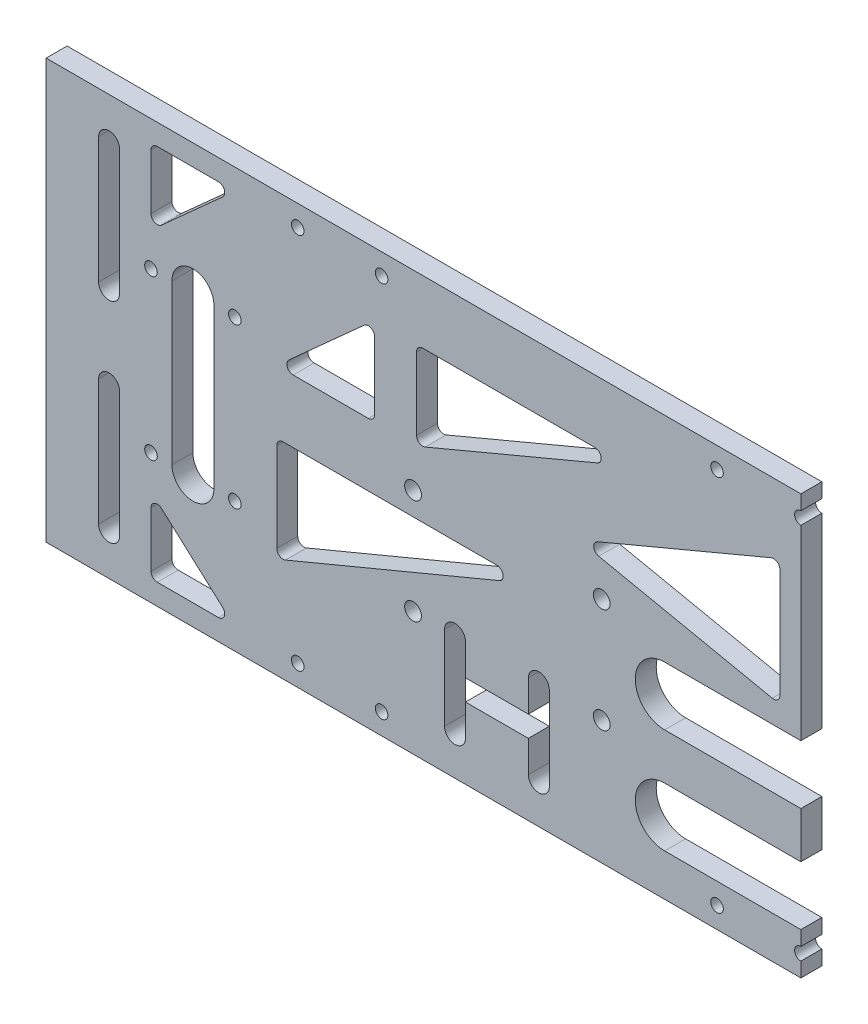
SolidWorks part; units mm, degrees
material "A-玻璃纤维"
ref_plane "前视基准面" through (0, 0, 0) normal (0, 0, 1) x (1, 0, 0)
ref_plane "上视基准面" through (0, 0, 0) normal (0, 1, 0) x (1, 0, 0)
ref_plane "右视基准面" through (0, 0, 0) normal (1, 0, 0) x (0, 0, -1)
sketch "草图1" plane through (0, 0, 0) normal (0, 0, 1) x (1, 0, 0)
  line L1 (0, 0) -> (320, 0)
  line L2 (0, 0) -> (0, 121)
  line L3 (0, 121) -> (320, 121)
  line L4 (320, 0) -> (320, 121)
  dimension "D1" = 320
  dimension "D2" = 121
extrude "凸台-拉伸1" add sketch "草图1" along normal blind 5
sketch "草图2" plane through (0, 0, 5) normal (0, 0, 1) x (1, 0, 0)
  line L0 (160, 121) -> (160, 0) construction
  line L1 (320, 121) -> (0, 121) construction
  line L2 (0, 0) -> (320, 0) construction
  line L3 (0, 121) -> (0, 0) construction
  line L4 (30, 0) -> (35, 0)
  line L5 (30, 0) -> (30, 30)
  line L6 (30, 30) -> (35, 30)
  line L7 (35, 0) -> (35, 30)
  line L8 (285, 0) -> (285, 30)
  line L9 (290, 30) -> (285, 30)
  line L10 (290, 0) -> (290, 30)
  line L11 (290, 0) -> (285, 0)
  dimension "D1" = 30
  dimension "D2" = 30
  dimension "D3" = 5
extrude "切除-拉伸1" cut sketch "草图2" against normal through all
sketch "草图3" plane through (0, 0, 5) normal (0, 0, 1) x (1, 0, 0)
  line L0 (40, 116) -> (60, 116) construction
  line L1 (160, 121) -> (160, 0) construction
  line L2 (320, 121) -> (0, 121) construction
  line L3 (35, 0) -> (285, 0) construction
  line L4 (140, 116) -> (160, 116) construction
  line L5 (0, 121) -> (0, 0) construction
  line L6 (280, 116) -> (260, 116) construction
  circle A0 centre (40, 116) radius 1.5
  circle A1 centre (60, 116) radius 1.5
  circle A2 centre (140, 116) radius 1.5
  circle A3 centre (160, 116) radius 1.5
  circle A4 centre (260, 116) radius 1.5
  circle A5 centre (280, 116) radius 1.5
  circle A6 centre (180, 116) radius 1.5
  dimension "D5" = 3
  dimension "D1" = 40
  dimension "D2" = 5
  dimension "D3" = 20
  dimension "D4" = 20
extrude "切除-拉伸2" cut sketch "草图3" against normal through all
sketch "草图4" plane through (0, 0, 5) normal (0, 0, 1) x (1, 0, 0)
  line L0 (160, 121) -> (160, 0) construction
  line L1 (5, 90) -> (25, 90) construction
  line L2 (5, 90) -> (5, 10) construction
  line L3 (5, 10) -> (25, 10) construction
  line L4 (25, 90) -> (25, 10) construction
  line L5 (320, 121) -> (0, 121) construction
  line L6 (35, 0) -> (285, 0) construction
  line L7 (0, 0) -> (30, 0) construction
  line L8 (0, 121) -> (0, 0) construction
  line L10 (295, 90) -> (295, 10) construction
  line L11 (315, 10) -> (295, 10) construction
  line L12 (315, 90) -> (315, 10) construction
  line L13 (315, 90) -> (295, 90) construction
  circle A0 centre (5, 90) radius 1.5
  circle A1 centre (25, 90) radius 1.5
  circle A2 centre (5, 10) radius 1.5
  circle A3 centre (25, 10) radius 1.5
  circle A4 centre (295, 10) radius 1.5
  circle A5 centre (315, 10) radius 1.5
  circle A6 centre (295, 90) radius 1.5
  circle A7 centre (315, 90) radius 1.5
  dimension "D5" = 3
  dimension "D1" = 10
  dimension "D2" = 80
  dimension "D3" = 5
  dimension "D4" = 20
extrude "切除-拉伸3" cut sketch "草图4" against normal through all
sketch "草图6" plane through (0, 0, 5) normal (0, 0, 1) x (1, 0, 0)
  line L0 (160, 121) -> (160, 0) construction
  line L1 (320, 121) -> (0, 121) construction
  line L2 (35, 0) -> (285, 0) construction
  line L3 (127.5, 63) -> (192.5, 63) construction
  line L4 (112.5, 50.5) -> (207.5, 50.5) construction
  line L5 (112.5, 50.5) -> (112.5, 75.5) construction
  line L6 (112.5, 75.5) -> (207.5, 75.5) construction
  line L7 (207.5, 50.5) -> (207.5, 75.5) construction
  line L8 (112.5, 50.5) -> (207.5, 75.5) construction
  line L9 (112.5, 75.5) -> (207.5, 50.5) construction
  line L10 (127.5, 70) -> (192.5, 70)
  line L11 (127.5, 56) -> (192.5, 56)
  circle A0 centre (112.5, 75.5) radius 2
  circle A1 centre (207.5, 75.5) radius 2
  circle A2 centre (207.5, 50.5) radius 2
  circle A3 centre (112.5, 50.5) radius 2
  arc A4 (127.5, 70) -> (127.5, 56) centre (127.5, 63) ccw
  arc A5 (192.5, 56) -> (192.5, 70) centre (192.5, 63) ccw
  point P6 (160, 63)
  point P17 (160, 63)
  dimension "D1" = 4
  dimension "D5" = 7
  dimension "D2" = 25
  dimension "D3" = 95
  dimension "D4" = 45.5
  dimension "D6" = 15
extrude "切除-拉伸5" cut sketch "草图6" against normal through all
sketch "草图5" plane through (0, 0, 5) normal (0, 0, 1) x (1, 0, 0)
  line L0 (5, 101.368) -> (5, 114.5)
  line L1 (6.5, 116) -> (21.0911, 116)
  line L2 (22.0945, 113.3851) -> (7.5034, 100.2531)
  line L6 (5, 90) -> (25, 90) construction
  line L7 (0, 121) -> (0, 0) construction
  line L8 (320, 121) -> (0, 121) construction
  line L9 (38.9089, 85) -> (56.8333, 85)
  line L10 (58.3333, 86.5) -> (58.3333, 102.632)
  line L11 (55.8299, 103.7469) -> (37.9055, 87.6149)
  line L12 (160, 121) -> (160, 0) construction
  line L13 (35, 0) -> (285, 0) construction
  line L14 (35, 68.5) -> (35, 47.25)
  line L15 (35, 0) -> (285, 0)
  line L16 (35, 0) -> (35, 30)
  line L17 (35, 30) -> (285, 30)
  line L18 (285, 0) -> (285, 30)
  line L19 (37.0769, 45.8654) -> (88.0769, 67.1154)
  line L20 (87.5, 70) -> (36.5, 70)
  line L24 (68.3333, 87.2569) -> (68.3333, 104.5)
  line L25 (69.8333, 106) -> (110.8883, 106)
  line L26 (111.4691, 103.117) -> (70.4142, 85.874)
  line L27 (111.7889, 84.0154) -> (153.1936, 75.3769)
  line L28 (155, 76.8453) -> (155, 102.8738)
  line L29 (152.9192, 104.2567) -> (111.5144, 86.8668)
  line L30 (315, 90) -> (295, 90) construction
  line L31 (167.0808, 104.2567) -> (208.4856, 86.8668)
  line L32 (165, 76.8453) -> (165, 102.8738)
  line L33 (208.2111, 84.0154) -> (166.8064, 75.3769)
  line L34 (208.5309, 103.117) -> (249.5858, 85.874)
  line L35 (250.1667, 106) -> (209.1117, 106)
  line L36 (251.6667, 87.2569) -> (251.6667, 104.5)
  line L40 (232.5, 70) -> (283.5, 70)
  line L41 (282.9231, 45.8654) -> (231.9231, 67.1154)
  line L42 (285, 68.5) -> (285, 47.25)
  line L43 (264.1701, 103.7469) -> (282.0945, 87.6149)
  line L44 (261.6667, 86.5) -> (261.6667, 102.632)
  line L45 (281.0911, 85) -> (263.1667, 85)
  line L46 (297.9055, 113.3851) -> (312.4966, 100.2531)
  line L47 (313.5, 116) -> (298.9089, 116)
  line L48 (315, 101.368) -> (315, 114.5)
  line L52 (192.5, 70) -> (127.5, 70) construction
  arc A2 (155, 102.8738) -> (152.9192, 104.2567) centre (153.5, 102.8738) ccw
  arc A4 (21.0911, 116) -> (22.0945, 113.3851) centre (21.0911, 114.5) cw
  arc A5 (5, 101.368) -> (7.5034, 100.2531) centre (6.5, 101.368) ccw
  arc A6 (5, 114.5) -> (6.5, 116) centre (6.5, 114.5) cw
  arc A7 (56.8333, 85) -> (58.3333, 86.5) centre (56.8333, 86.5) ccw
  arc A8 (38.9089, 85) -> (37.9055, 87.6149) centre (38.9089, 86.5) cw
  arc A9 (58.3333, 102.632) -> (55.8299, 103.7469) centre (56.8333, 102.632) ccw
  arc A10 (88.0769, 67.1154) -> (87.5, 70) centre (87.5, 68.5) ccw
  arc A11 (35, 47.25) -> (37.0769, 45.8654) centre (36.5, 47.25) ccw
  arc A12 (35, 68.5) -> (36.5, 70) centre (36.5, 68.5) cw
  arc A17 (153.1936, 75.3769) -> (155, 76.8453) centre (153.5, 76.8453) ccw
  arc A18 (111.7889, 84.0154) -> (111.5144, 86.8668) centre (112.0953, 85.4838) cw
  arc A19 (68.3333, 87.2569) -> (70.4142, 85.874) centre (69.8333, 87.2569) ccw
  arc A20 (68.3333, 104.5) -> (69.8333, 106) centre (69.8333, 104.5) cw
  arc A21 (110.8883, 106) -> (111.4691, 103.117) centre (110.8883, 104.5) cw
  arc A22 (209.1117, 106) -> (208.5309, 103.117) centre (209.1117, 104.5) ccw
  arc A23 (251.6667, 104.5) -> (250.1667, 106) centre (250.1667, 104.5) ccw
  arc A24 (251.6667, 87.2569) -> (249.5858, 85.874) centre (250.1667, 87.2569) cw
  arc A25 (208.2111, 84.0154) -> (208.4856, 86.8668) centre (207.9047, 85.4838) ccw
  arc A26 (166.8064, 75.3769) -> (165, 76.8453) centre (166.5, 76.8453) cw
  arc A30 (285, 68.5) -> (283.5, 70) centre (283.5, 68.5) ccw
  arc A31 (285, 47.25) -> (282.9231, 45.8654) centre (283.5, 47.25) cw
  arc A32 (231.9231, 67.1154) -> (232.5, 70) centre (232.5, 68.5) cw
  arc A33 (261.6667, 102.632) -> (264.1701, 103.7469) centre (263.1667, 102.632) cw
  arc A34 (281.0911, 85) -> (282.0945, 87.6149) centre (281.0911, 86.5) ccw
  arc A35 (263.1667, 85) -> (261.6667, 86.5) centre (263.1667, 86.5) cw
  arc A36 (315, 114.5) -> (313.5, 116) centre (313.5, 114.5) ccw
  arc A37 (315, 101.368) -> (312.4966, 100.2531) centre (313.5, 101.368) cw
  arc A38 (298.9089, 116) -> (297.9055, 113.3851) centre (298.9089, 114.5) ccw
  arc A39 (165, 102.8738) -> (167.0808, 104.2567) centre (166.5, 102.8738) cw
  point P23 (25, 116)
  point P26 (5, 98)
  point P29 (5, 116)
  point P40 (35, 85)
  point P43 (58.3333, 106)
  point P56 (95, 70)
  point P59 (35, 45)
  point P62 (35, 70)
  point P84 (155, 105.1307)
  point P87 (155, 75)
  point P90 (107.0698, 85)
  point P93 (68.3333, 85)
  point P96 (68.3333, 106)
  point P99 (118.3333, 106)
  point P156 (201.6667, 106)
  point P157 (251.6667, 106)
  point P158 (251.6667, 85)
  point P159 (212.9302, 85)
  point P160 (165, 75)
  point P161 (165, 105.1307)
  point P162 (285, 70)
  point P163 (285, 45)
  point P164 (225, 70)
  point P165 (261.6667, 106)
  point P166 (285, 85)
  point P167 (315, 116)
  point P168 (315, 98)
  point P169 (295, 116)
  point P186 (20, 15)
  point P189 (8, 15)
  point P192 (20, 25)
  point P202 (300, 25)
  point P203 (312, 15)
  point P204 (300, 15)
  dimension "D8" = 1.5
  dimension "D12" = 1.5
  dimension "D16" = 1.5
  dimension "D27" = 1.5
  dimension "D4" = 5
  dimension "D5" = 5
  dimension "D6" = 20
  dimension "D7" = 18
  dimension "D9" = 5
  dimension "D10" = 10
  dimension "D11" = 10
  dimension "D13" = 15
  dimension "D14" = 15
  dimension "D15" = 60
  dimension "D21" = 15
  dimension "D22" = 10
  dimension "D23" = 50
  dimension "D24" = 15
  dimension "D25" = 10
  dimension "D26" = 5
  dimension "D29" = 8
  dimension "D31" = 10
extrude "切除-拉伸4" cut sketch "草图5" against normal through all
sketch "草图7" plane through (0, 0, 0) normal (0, 0, -1) x (-1, 0, 0)
  line L0 (-290, 0) -> (-290, 30)
  line L1 (-290, 30) -> (-30, 30)
  line L2 (-30, 30) -> (-30, 0)
  line L3 (-30, 0) -> (-290, 0)
extrude "凸台-拉伸2" add sketch "草图7" against normal blind 5
sketch "草图8" plane through (0, 0, 0) normal (0, 0, -1) x (-1, 0, 0)
  line L0 (-320, 0) -> (-320, 21)
  line L1 (-320, 0) -> (-320, 121) construction
  line L2 (-320, 21) -> (0, 21)
  line L3 (0, 121) -> (0, 0) construction
  line L4 (0, 21) -> (0, 0)
  line L5 (0, 0) -> (-320, 0)
extrude "切除-拉伸6" cut sketch "草图8" against normal blind 5
sketch "草图9" plane through (0, 0, 0) normal (0, 0, -1) x (-1, 0, 0)
  line L0 (-160, 21) -> (-335, 21)
  line L1 (0, 21) -> (-320, 21) construction
  line L2 (-335, 21) -> (-335, 121)
  line L3 (-335, 121) -> (15, 121)
  line L4 (15, 121) -> (15, 21)
  line L5 (15, 21) -> (-160, 21)
  line L6 (0, 21) -> (0, 121)
  line L7 (-320, 21) -> (-320, 121)
extrude "凸台-拉伸3" add sketch "草图9" against normal blind 5 contours L0 L7 L3 L2 | L6 L5 L4 L3
sketch "草图10" plane through (0, 0, 0) normal (0, 0, -1) x (-1, 0, 0)
  line L0 (-335, 71) -> (-325, 71)
  line L1 (-335, 21) -> (-335, 121) construction
  line L2 (-325, 71) -> (-325, 121)
  line L3 (-335, 121) -> (15, 121) construction
  line L4 (-325, 71) -> (-325, 21)
  line L5 (15, 21) -> (-335, 21) construction
  line L6 (15, 71) -> (5, 71)
  line L7 (15, 121) -> (15, 21) construction
  line L8 (5, 71) -> (5, 121)
  line L9 (5, 71) -> (5, 21)
  line L10 (-325, 71) -> (-325, 81)
  line L11 (-325, 81) -> (-325, 111)
  line L12 (-325, 71) -> (-325, 61)
  line L13 (-325, 61) -> (-325, 31)
  line L14 (-325, 81) -> (-325, 111) construction
  line L15 (-327.5, 81) -> (-327.5, 111)
  line L16 (-322.5, 81) -> (-322.5, 111)
  line L17 (-325, 61) -> (-325, 31) construction
  line L18 (-322.5, 61) -> (-322.5, 31)
  line L19 (-327.5, 61) -> (-327.5, 31)
  line L20 (-160, 21) -> (-160, 121)
  line L21 (5, 61) -> (5, 31) construction
  line L22 (2.5, 61) -> (2.5, 31)
  line L23 (7.5, 61) -> (7.5, 31)
  line L24 (5, 81) -> (5, 111) construction
  line L25 (7.5, 81) -> (7.5, 111)
  line L26 (2.5, 81) -> (2.5, 111)
  arc A0 (-327.5, 81) -> (-322.5, 81) centre (-325, 81) ccw
  arc A1 (-322.5, 111) -> (-327.5, 111) centre (-325, 111) ccw
  arc A2 (-322.5, 61) -> (-327.5, 61) centre (-325, 61) ccw
  arc A3 (-327.5, 31) -> (-322.5, 31) centre (-325, 31) ccw
  arc A4 (2.5, 61) -> (7.5, 61) centre (5, 61) cw
  arc A5 (7.5, 31) -> (2.5, 31) centre (5, 31) cw
  arc A6 (7.5, 81) -> (2.5, 81) centre (5, 81) cw
  arc A7 (2.5, 111) -> (7.5, 111) centre (5, 111) cw
  point P20 (-325, 96)
  point P25 (-325, 46)
  point P34 (5, 46)
  point P41 (5, 96)
  dimension "D1" = 10
  dimension "D2" = 10
  dimension "D3" = 30
  dimension "D4" = 10
  dimension "D5" = 30
extrude "切除-拉伸7" cut sketch "草图10" against normal blind 5 contours L16 A1 L2 L10 A0 | L2 A1 L15 A0 L10 | L4 A3 L18 A2 L12 | L19 A3 L4 L12 A2 | A7 L8 A6 L25 | A7 L26 A6 L8 | A5 L23 A4 L9 | A5 L9 A4 L22
sketch "草图13" plane through (0, 0, 0) normal (0, 0, -1) x (-1, 0, 0)
  line L12 (-192.5, 63) -> (-192.5, 38)
  line L13 (-127.5, 63) -> (-127.5, 38)
  line L14 (-192.5, 38) -> (-127.5, 38) construction
  line L15 (-192.5, 45) -> (-127.5, 45)
  line L16 (-192.5, 31) -> (-127.5, 31)
  line L18 (-305, 63.5) -> (-305, 83.5)
  line L19 (-305, 63.5) -> (-305, 48.5)
  line L23 (-160, 21) -> (-160, 121)
  line L24 (15, 21) -> (-335, 21) construction
  line L25 (-335, 121) -> (15, 121) construction
  arc A1 (-192.5, 45) -> (-192.5, 31) centre (-192.5, 38) ccw
  arc A2 (-127.5, 31) -> (-127.5, 45) centre (-127.5, 38) ccw
  point P16 (-160, 38)
  dimension "D1" = 25
  dimension "D3" = 15
  dimension "D2" = 25
  dimension "D4" = 20
extrude "切除-拉伸8" cut sketch "草图13" against normal blind 5
sketch "草图15" plane through (0, 0, 0) normal (0, 0, -1) x (-1, 0, 0)
  line L0 (-313.5, 116) -> (-298.9089, 116)
  line L1 (-297.9055, 113.3851) -> (-312.4966, 100.2531)
  line L2 (-315, 114.5) -> (-315, 101.368)
  line L3 (-21.0911, 116) -> (-6.5, 116)
  line L4 (-5, 114.5) -> (-5, 101.368)
  line L5 (-7.5034, 100.2531) -> (-22.0945, 113.3851)
  line L6 (-335, 71) -> (15, 71)
  line L7 (-335, 21) -> (-335, 121) construction
  line L8 (15, 121) -> (15, 21) construction
  line L9 (-21.0911, 26) -> (-6.5, 26)
  line L10 (-5, 27.5) -> (-5, 40.632)
  line L11 (-7.5034, 41.7469) -> (-22.0945, 28.6149)
  line L12 (-315, 27.5) -> (-315, 40.632)
  line L13 (-313.5, 26) -> (-298.9089, 26)
  line L14 (-297.9055, 28.6149) -> (-312.4966, 41.7469)
  circle A0 centre (-280, 116) radius 1.5
  circle A1 centre (-260, 116) radius 1.5
  circle A2 centre (-180, 116) radius 1.5
  circle A3 centre (-160, 116) radius 1.5
  circle A4 centre (-140, 116) radius 1.5
  circle A5 centre (-60, 116) radius 1.5
  circle A6 centre (-40, 116) radius 1.5
  circle A7 centre (-25, 90) radius 1.5
  circle A8 centre (-5, 90) radius 1.5
  circle A9 centre (-315, 90) radius 1.5
  circle A10 centre (-295, 90) radius 1.5
  arc A11 (-315, 101.368) -> (-312.4966, 100.2531) centre (-313.5, 101.368) ccw
  arc A12 (-313.5, 116) -> (-315, 114.5) centre (-313.5, 114.5) ccw
  arc A13 (-297.9055, 113.3851) -> (-298.9089, 116) centre (-298.9089, 114.5) ccw
  arc A14 (-21.0911, 116) -> (-22.0945, 113.3851) centre (-21.0911, 114.5) ccw
  arc A15 (-5, 114.5) -> (-6.5, 116) centre (-6.5, 114.5) ccw
  arc A16 (-7.5034, 100.2531) -> (-5, 101.368) centre (-6.5, 101.368) ccw
  circle A17 centre (-25, 52) radius 1.5
  circle A18 centre (-5, 52) radius 1.5
  arc A19 (-5, 27.5) -> (-6.5, 26) centre (-6.5, 27.5) cw
  arc A20 (-7.5034, 41.7469) -> (-5, 40.632) centre (-6.5, 40.632) cw
  arc A21 (-21.0911, 26) -> (-22.0945, 28.6149) centre (-21.0911, 27.5) cw
  circle A22 centre (-40, 26) radius 1.5
  circle A23 centre (-60, 26) radius 1.5
  circle A24 centre (-140, 26) radius 1.5
  circle A25 centre (-160, 26) radius 1.5
  circle A26 centre (-180, 26) radius 1.5
  circle A27 centre (-260, 26) radius 1.5
  circle A28 centre (-280, 26) radius 1.5
  arc A29 (-313.5, 26) -> (-315, 27.5) centre (-313.5, 27.5) cw
  arc A30 (-297.9055, 28.6149) -> (-298.9089, 26) centre (-298.9089, 27.5) cw
  arc A31 (-315, 40.632) -> (-312.4966, 41.7469) centre (-313.5, 40.632) cw
  circle A32 centre (-295, 52) radius 1.5
  circle A33 centre (-315, 52) radius 1.5
extrude "切除-拉伸9" cut sketch "草图15" against normal through all contours A33 | A31 L12 A29 L13 A30 L14 | A32 | A28 | A27 | A26 | A25 | A24 | A23 | A22 | A21 L9 A19 L10 A20 L11 | A18 | A17
sketch "草图16" plane through (0, 0, 0) normal (0, 0, -1) x (-1, 0, 0)
  line L0 (-335, 71) -> (15, 71)
  line L1 (-335, 21) -> (-335, 121) construction
  line L2 (15, 121) -> (15, 21) construction
  line L3 (-315, 90) -> (-295, 90)
  line L4 (-315, 52) -> (-295, 52)
  line L5 (-305, 52) -> (-305, 90)
  line L6 (-305, 52) -> (-305, 90) construction
  line L7 (-310, 52) -> (-310, 90)
  line L8 (-300, 52) -> (-300, 90)
  line L9 (-160, 21) -> (-160, 121)
  line L10 (15, 21) -> (-335, 21) construction
  line L11 (-335, 121) -> (15, 121) construction
  line L12 (-15, 52) -> (-15, 90) construction
  line L13 (-10, 52) -> (-10, 90)
  line L14 (-20, 52) -> (-20, 90)
  arc A0 (-310, 52) -> (-300, 52) centre (-305, 52) ccw
  arc A1 (-300, 90) -> (-310, 90) centre (-305, 90) ccw
  arc A2 (-10, 52) -> (-20, 52) centre (-15, 52) cw
  arc A3 (-20, 90) -> (-10, 90) centre (-15, 90) cw
  point P16 (-305, 71)
  point P29 (-15, 71)
extrude "切除-拉伸10" cut sketch "草图16" against normal through all contours L4 L8 L0 L5 | L4 A0 | L7 L4 L5 L0 | L0 L8 L3 L5 | L7 L0 L5 L3 | L3 A1 | A2 L13 L0 L14 | A3 L14 L0 L13
sketch "草图17" plane through (0, 0, 0) normal (0, 0, -1) x (-1, 0, 0)
  line L0 (-207.5, 50.5) -> (-257.5, 50.5)
  line L1 (-257.5, 50.5) -> (-257.5, 30.5)
  line L2 (-257.5, 30.5) -> (-207.5, 30.5)
  line L3 (-207.5, 30.5) -> (-207.5, 50.5)
  line L4 (-207.5, 40.5) -> (-257.5, 40.5)
  line L5 (-257.5, 50.5) -> (-247.5, 50.5)
  line L6 (-247.5, 50.5) -> (-247.5, 30.5)
  line L7 (-207.5, 50.5) -> (-217.5, 50.5)
  line L8 (-217.5, 50.5) -> (-217.5, 30.5)
  line L9 (-247.5, 50.5) -> (-242.5, 50.5)
  line L10 (-242.5, 50.5) -> (-242.5, 30.5)
  line L11 (-217.5, 50.5) -> (-222.5, 50.5)
  line L12 (-222.5, 50.5) -> (-222.5, 30.5)
  line L13 (-242.5, 50.5) -> (-242.5, 30.5) construction
  line L14 (-240, 50.5) -> (-240, 30.5)
  line L15 (-245, 50.5) -> (-245, 30.5)
  line L16 (-222.5, 50.5) -> (-222.5, 30.5) construction
  line L17 (-220, 50.5) -> (-220, 30.5)
  line L18 (-225, 50.5) -> (-225, 30.5)
  line L19 (-242.5, 40.5) -> (-222.5, 40.5) construction
  line L20 (-242.5, 43) -> (-222.5, 43)
  line L21 (-242.5, 38) -> (-222.5, 38)
  line L22 (-160, 21) -> (-160, 121)
  line L23 (15, 21) -> (-335, 21) construction
  line L24 (-335, 121) -> (15, 121) construction
  line L25 (-97.5, 50.5) -> (-97.5, 30.5) construction
  line L26 (-100, 50.5) -> (-100, 30.5)
  line L27 (-95, 50.5) -> (-95, 30.5)
  line L28 (-77.5, 40.5) -> (-97.5, 40.5) construction
  line L29 (-77.5, 43) -> (-97.5, 43)
  line L30 (-77.5, 38) -> (-97.5, 38)
  line L31 (-77.5, 50.5) -> (-77.5, 30.5) construction
  line L32 (-80, 50.5) -> (-80, 30.5)
  line L33 (-75, 50.5) -> (-75, 30.5)
  arc A0 (-240, 50.5) -> (-245, 50.5) centre (-242.5, 50.5) ccw
  arc A1 (-245, 30.5) -> (-240, 30.5) centre (-242.5, 30.5) ccw
  arc A2 (-220, 50.5) -> (-225, 50.5) centre (-222.5, 50.5) ccw
  arc A3 (-225, 30.5) -> (-220, 30.5) centre (-222.5, 30.5) ccw
  arc A4 (-242.5, 43) -> (-242.5, 38) centre (-242.5, 40.5) ccw
  arc A5 (-222.5, 38) -> (-222.5, 43) centre (-222.5, 40.5) ccw
  arc A6 (-100, 50.5) -> (-95, 50.5) centre (-97.5, 50.5) cw
  arc A7 (-95, 30.5) -> (-100, 30.5) centre (-97.5, 30.5) cw
  arc A8 (-77.5, 43) -> (-77.5, 38) centre (-77.5, 40.5) cw
  arc A9 (-97.5, 38) -> (-97.5, 43) centre (-97.5, 40.5) cw
  arc A10 (-80, 50.5) -> (-75, 50.5) centre (-77.5, 50.5) cw
  arc A11 (-75, 30.5) -> (-80, 30.5) centre (-77.5, 30.5) cw
  point P11 (-242.5, 40.5)
  point P20 (-222.5, 40.5)
  point P25 (-232.5, 40.5)
  point P40 (-97.5, 40.5)
  point P47 (-87.5, 40.5)
  point P54 (-77.5, 40.5)
  dimension "D1" = 20
extrude "切除-拉伸11" cut sketch "草图17" against normal through all contours A11 L33 A8 L30 L32 | A8 L29 L32 L30 | A10 L32 L29 A8 L33 | L32 L29 L27 L30 | A9 L30 L27 L29 | L26 A9 L29 L27 A6 | L30 A9 L26 A7 L27 | L10 L20 L14 L0 | A4 L10 L0 L15 | L0 A0 | L20 L14 L4 L18 | L20 L10 L4 L14 | L10 A4 L4 | L4 A4 L10 | L10 L21 L14 L4 | L14 L21 L18 L4 | L21 L10 L2 L14 | A4 L15 L2 L10 | L2 A1 | L2 A3 | A5 L12 L2 L17 | L21 L18 L2 L12 | L18 L21 L12 L4 | L12 A5 L4 | L4 A5 L12 | L20 L18 L4 L12 | L18 L20 L12 L0 | A5 L17 L11 L12 | L11 A2 L0
sketch "草图18" plane through (0, 0, 0) normal (0, 0, -1) x (-1, 0, 0)
  line L0 (-335, 21) -> (-340, 21)
  line L1 (-340, 21) -> (-340, 121)
  line L2 (-340, 121) -> (-335, 121)
  line L3 (-335, 121) -> (-335, 21)
  line L4 (15, 21) -> (20, 21)
  line L5 (20, 21) -> (20, 121)
  line L6 (20, 121) -> (15, 121)
  line L7 (15, 121) -> (15, 21)
extrude "凸台-拉伸4" add sketch "草图18" against normal blind 5
sketch "草图19" plane through (0, 0, 5) normal (0, 0, 1) x (1, 0, 0)
  line L0 (-20, 121) -> (-20, 21)
  line L1 (-20, 21) -> (160, 21)
  line L2 (-20, 21) -> (340, 21) construction
  line L3 (160, 21) -> (160, 121)
  line L4 (340, 121) -> (-20, 121) construction
  line L5 (160, 121) -> (-20, 121)
  line L6 (160, 121) -> (340, 121)
  line L7 (340, 121) -> (340, 21)
  line L8 (340, 21) -> (160, 21)
extrude "切除-拉伸13" cut sketch "草图19" against normal blind 10 contours L8 L7 L6 L3
sketch "草图20" plane through (0, 0, 5) normal (0, 0, 1) x (1, 0, 0)
  line L0 (112.5, 75.5) -> (10, 75.5)
  line L1 (10, 52) -> (10, 90) construction
  line L2 (112.5, 50.5) -> (-10.8064, 50.5)
  line L3 (112.5, 75.5) -> (67.5, 75.5)
  line L4 (112.5, 50.5) -> (67.5, 50.5)
  circle A0 centre (67.5, 75.5) radius 2
  circle A1 centre (67.5, 50.5) radius 2
extrude "切除-拉伸14" cut sketch "草图20" against normal blind 10 contours L0 A0 L3 | L3 A0 L0 | L2 A1 L4 | L4 A1 L2
